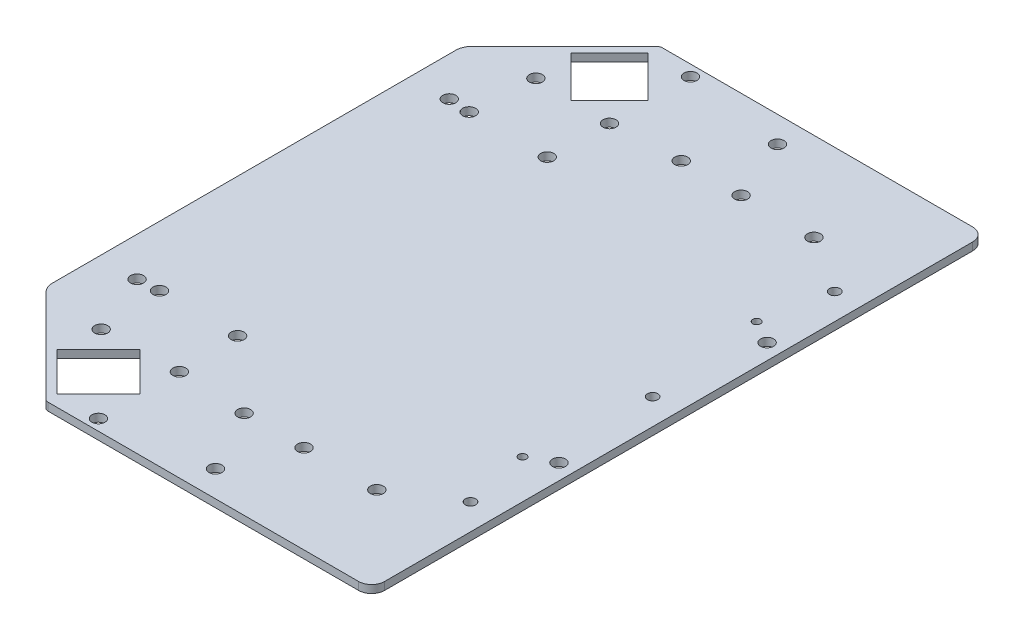
SolidWorks part; units mm, degrees
ref_plane "前视基准面" through (0, 0, 0) normal (0, 0, 1) x (1, 0, 0)
ref_plane "上视基准面" through (0, 0, 0) normal (0, 1, 0) x (1, 0, 0)
ref_plane "右视基准面" through (0, 0, 0) normal (1, 0, 0) x (0, 0, -1)
other "Configuration Table"
ref_plane "基准面1" through (0, 0, 0) normal (0, -1, 0) x (1, 0, 0)
sketch "草图1" plane through (0, 0, 0) normal (0, -1, 0) x (1, 0, 0)
  line L0 (-154.3087, -118) -> (-35, -118)
  line L1 (-30, -113) -> (-30, 113)
  line L2 (-35, 118) -> (-154.3087, 118)
  line L3 (-155.7229, 117.4142) -> (-191.3797, 81.7574)
  line L4 (-193.1371, 77.5147) -> (-193.1371, -77.5147)
  line L5 (-191.3797, -81.7574) -> (-155.7229, -117.4142)
  line L6 (-170.1561, 98.7383) -> (-155.3069, 113.5876)
  line L7 (-155.3069, 113.5876) -> (-139.397, 97.6777)
  line L8 (-139.397, 97.6777) -> (-154.2462, 82.8284)
  line L9 (-154.2462, 82.8284) -> (-170.1561, 98.7383)
  line L10 (-170.1561, -98.7383) -> (-154.2462, -82.8284)
  line L11 (-154.2462, -82.8284) -> (-139.397, -97.6777)
  line L12 (-139.397, -97.6777) -> (-155.3069, -113.5876)
  line L13 (-155.3069, -113.5876) -> (-170.1561, -98.7383)
  arc A0 (-35, -118) -> (-30, -113) centre (-35, -113) ccw
  arc A1 (-30, 113) -> (-35, 118) centre (-35, 113) ccw
  arc A2 (-154.3087, 118) -> (-155.7229, 117.4142) centre (-154.3087, 116) ccw
  arc A3 (-191.3797, 81.7574) -> (-193.1371, 77.5147) centre (-187.1371, 77.5147) ccw
  arc A4 (-193.1371, -77.5147) -> (-191.3797, -81.7574) centre (-187.1371, -77.5147) ccw
  arc A5 (-155.7229, -117.4142) -> (-154.3087, -118) centre (-154.3087, -116) ccw
  circle A6 centre (-140, 59.5) radius 2.5
  circle A7 centre (-170, -59.5) radius 2.5
  circle A8 centre (-140, -59.5) radius 2.5
  circle A9 centre (-178.1371, 60) radius 2.5
  circle A10 centre (-178.1371, -60) radius 2.5
  circle A11 centre (-168.3883, -83.5355) radius 2.5
  circle A12 centre (-168.3883, 83.5355) radius 2.5
  circle A13 centre (-45, -45) radius 1.5
  circle A14 centre (-45, 45) radius 1.5
  circle A15 centre (-36, -40) radius 2.5
  circle A16 centre (-36, 40) radius 2.5
  circle A17 centre (-62, 84) radius 2.5
  circle A18 centre (-90, 84) radius 2.5
  circle A19 centre (-113, 84) radius 2.5
  circle A20 centre (-62, -84) radius 2.5
  circle A21 centre (-90, -84) radius 2.5
  circle A22 centre (-113, -84) radius 2.5
  circle A23 centre (-100, -108) radius 2.5
  circle A24 centre (-100, 108) radius 2.5
  circle A25 centre (-139.2202, 113.7643) radius 2.5
  circle A26 centre (-139.2202, 82.6517) radius 2.5
  circle A27 centre (-139.2202, -113.7643) radius 2.5
  circle A28 centre (-139.2202, -82.6517) radius 2.5
  circle A29 centre (-40, 70) radius 2
  circle A30 centre (-40, -70) radius 2
  circle A31 centre (-40, 0) radius 2
  circle A32 centre (-170, 59.5) radius 2.5
  dimension "D1" = 10
extrude "凸台-拉伸1" add sketch "草图1" against normal blind 3
